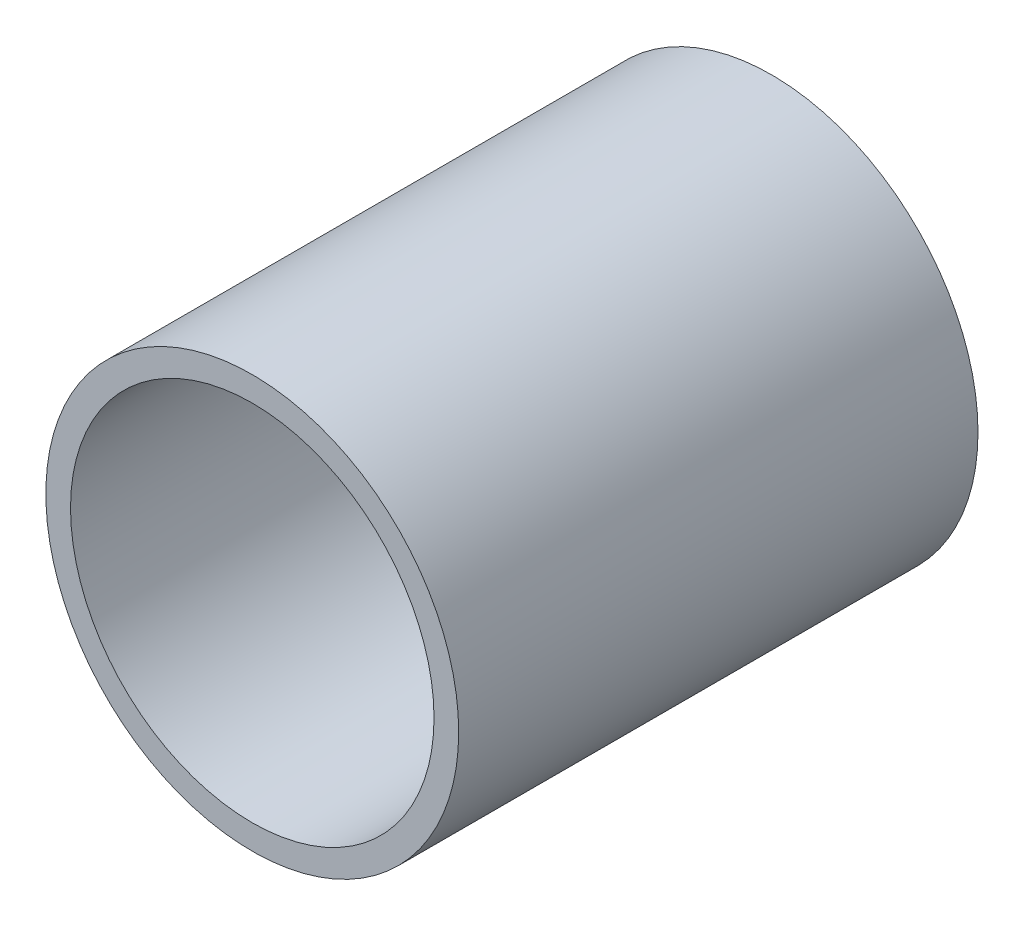
SolidWorks part; units mm, degrees
material "AISI Type 316L stainless steel"
ref_plane "Front Plane" through (0, 0, 0) normal (0, 0, 1) x (1, 0, 0)
ref_plane "Top Plane" through (0, 0, 0) normal (0, 1, 0) x (1, 0, 0)
ref_plane "Right Plane" through (0, 0, 0) normal (1, 0, 0) x (0, 0, -1)
sketch "Sketch1" plane through (0, 0, 0) normal (0, 0, 1) x (1, 0, 0)
  circle A0 centre (0, 0) radius 7.95
  circle A1 centre (0, 0) radius 7
  dimension "D1" = 14
  dimension "D2" = 15.9
extrude "Boss-Extrude1" add sketch "Sketch1" along normal blind 20
